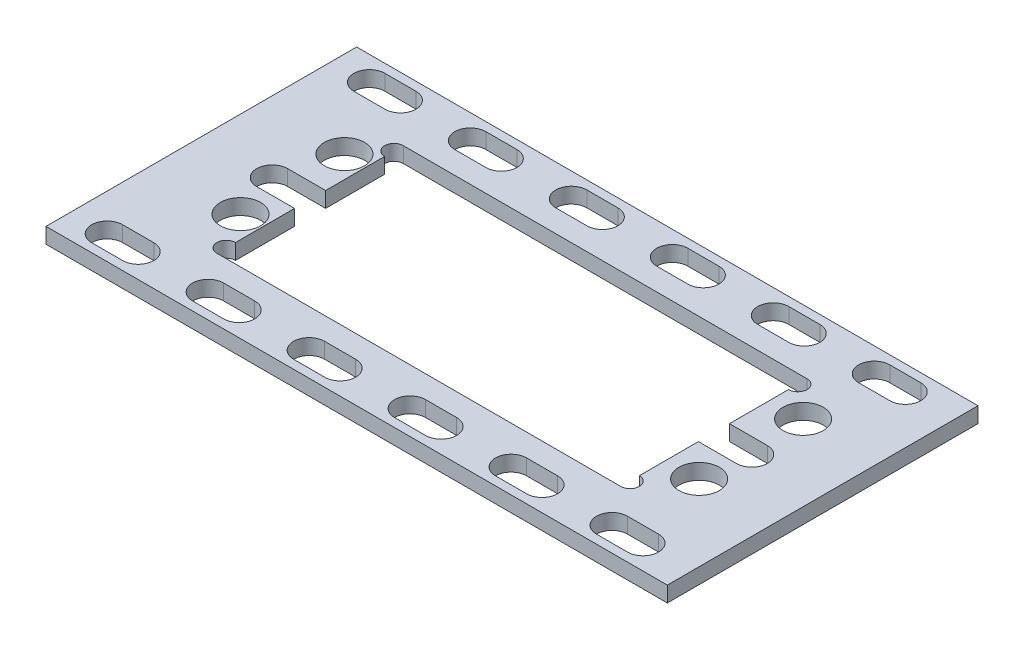
SolidWorks part; units mm, degrees
ref_plane "Front Plane" through (0, 0, 0) normal (0, 0, 1) x (1, 0, 0)
ref_plane "Top Plane" through (0, 0, 0) normal (0, 1, 0) x (1, 0, 0)
ref_plane "Right Plane" through (0, 0, 0) normal (1, 0, 0) x (0, 0, -1)
sketch "Sketch1" plane through (0, 0, 0) normal (0, 1, 0) x (1, 0, 0)
  line L0 (-33.02, 0) -> (33.02, 0) construction
  line L1 (-50.8, 25.4) -> (50.8, 25.4)
  line L2 (-50.8, 25.4) -> (-50.8, -25.4)
  line L3 (-50.8, -25.4) -> (50.8, -25.4)
  line L4 (50.8, 25.4) -> (50.8, -25.4)
  line L5 (-50.8, 25.4) -> (50.8, -25.4) construction
  line L6 (-50.8, -25.4) -> (50.8, 25.4) construction
  line L7 (-33.02, 15.24) -> (33.02, 15.24)
  line L8 (-33.02, 12.192) -> (-33.02, -12.192)
  line L9 (-33.02, -15.24) -> (33.02, -15.24)
  line L10 (33.02, 12.192) -> (33.02, -12.192)
  line L11 (-31.5887, 14.5794) -> (0, 0) construction
  line L12 (-33.02, -15.24) -> (33.02, 15.24) construction
  arc A0 (-33.02, 15.24) -> (-33.02, 12.192) centre (-33.02, 13.716) ccw
  arc A1 (-33.02, -12.192) -> (-33.02, -15.24) centre (-33.02, -13.716) ccw
  arc A2 (33.02, 12.192) -> (33.02, 15.24) centre (33.02, 13.716) ccw
  arc A3 (33.02, -15.24) -> (33.02, -12.192) centre (33.02, -13.716) ccw
  point P0 (0, 0)
  point P6 (0, 0)
  dimension "D5" = 1.524
  dimension "D6" = 1.524
  dimension "D1" = 101.6
  dimension "D2" = 50.8
  dimension "D3" = 66.04
  dimension "D4" = 30.48
extrude "Boss-Extrude1" add sketch "Sketch1" along normal blind 2.54
sketch "Sketch2" plane through (0, 2.54, 0) normal (0, 1, 0) x (1, 0, 0)
  line L0 (-44.7595, -21.439) -> (-39.6795, -21.439) construction
  line L1 (-44.7595, -18.899) -> (-39.6795, -18.899)
  line L2 (-44.7595, -23.979) -> (-39.6795, -23.979)
  line L3 (-28.2495, -23.979) -> (-23.1695, -23.979)
  line L4 (-28.2495, -18.899) -> (-23.1695, -18.899)
  line L5 (-28.2495, -21.439) -> (-23.1695, -21.439) construction
  line L6 (-11.7395, -23.979) -> (-6.6595, -23.979)
  line L7 (-11.7395, -18.899) -> (-6.6595, -18.899)
  line L8 (-11.7395, -21.439) -> (-6.6595, -21.439) construction
  line L9 (4.7705, -23.979) -> (9.8505, -23.979)
  line L10 (4.7705, -18.899) -> (9.8505, -18.899)
  line L11 (4.7705, -21.439) -> (9.8505, -21.439) construction
  line L12 (21.2805, -23.979) -> (26.3605, -23.979)
  line L13 (21.2805, -18.899) -> (26.3605, -18.899)
  line L14 (21.2805, -21.439) -> (26.3605, -21.439) construction
  line L15 (37.7905, -23.979) -> (42.8705, -23.979)
  line L16 (37.7905, -18.899) -> (42.8705, -18.899)
  line L17 (37.7905, -21.439) -> (42.8705, -21.439) construction
  line L18 (-50.8, 0) -> (50.607, 0) construction
  line L19 (-50.8, 25.4) -> (-50.8, -25.4) construction
  line L20 (-1.397, 0) -> (1.397, 0) construction
  line L21 (-28.2495, 21.439) -> (-23.1695, 21.439) construction
  line L22 (-28.2495, 18.899) -> (-23.1695, 18.899)
  line L23 (-28.2495, 23.979) -> (-23.1695, 23.979)
  line L24 (37.7905, 21.439) -> (42.8705, 21.439) construction
  line L25 (37.7905, 18.899) -> (42.8705, 18.899)
  line L26 (37.7905, 23.979) -> (42.8705, 23.979)
  line L27 (21.2805, 21.439) -> (26.3605, 21.439) construction
  line L28 (21.2805, 18.899) -> (26.3605, 18.899)
  line L29 (21.2805, 23.979) -> (26.3605, 23.979)
  line L30 (4.7705, 21.439) -> (9.8505, 21.439) construction
  line L31 (4.7705, 18.899) -> (9.8505, 18.899)
  line L32 (4.7705, 23.979) -> (9.8505, 23.979)
  line L33 (-11.7395, 21.439) -> (-6.6595, 21.439) construction
  line L34 (-11.7395, 18.899) -> (-6.6595, 18.899)
  line L35 (-11.7395, 23.979) -> (-6.6595, 23.979)
  line L36 (-44.7595, 21.439) -> (-39.6795, 21.439) construction
  line L37 (-44.7595, 18.899) -> (-39.6795, 18.899)
  line L38 (-44.7595, 23.979) -> (-39.6795, 23.979)
  arc A0 (-44.7595, -18.899) -> (-44.7595, -23.979) centre (-44.7595, -21.439) ccw
  arc A1 (-39.6795, -23.979) -> (-39.6795, -18.899) centre (-39.6795, -21.439) ccw
  arc A2 (-28.2495, -18.899) -> (-28.2495, -23.979) centre (-28.2495, -21.439) ccw
  arc A3 (-23.1695, -23.979) -> (-23.1695, -18.899) centre (-23.1695, -21.439) ccw
  arc A4 (-11.7395, -18.899) -> (-11.7395, -23.979) centre (-11.7395, -21.439) ccw
  arc A5 (-6.6595, -23.979) -> (-6.6595, -18.899) centre (-6.6595, -21.439) ccw
  arc A6 (4.7705, -18.899) -> (4.7705, -23.979) centre (4.7705, -21.439) ccw
  arc A7 (9.8505, -23.979) -> (9.8505, -18.899) centre (9.8505, -21.439) ccw
  arc A8 (21.2805, -18.899) -> (21.2805, -23.979) centre (21.2805, -21.439) ccw
  arc A9 (26.3605, -23.979) -> (26.3605, -18.899) centre (26.3605, -21.439) ccw
  arc A10 (37.7905, -18.899) -> (37.7905, -23.979) centre (37.7905, -21.439) ccw
  arc A11 (42.8705, -23.979) -> (42.8705, -18.899) centre (42.8705, -21.439) ccw
  arc A12 (-28.2495, 18.899) -> (-28.2495, 23.979) centre (-28.2495, 21.439) cw
  arc A13 (-23.1695, 23.979) -> (-23.1695, 18.899) centre (-23.1695, 21.439) cw
  arc A14 (37.7905, 18.899) -> (37.7905, 23.979) centre (37.7905, 21.439) cw
  arc A15 (42.8705, 23.979) -> (42.8705, 18.899) centre (42.8705, 21.439) cw
  arc A16 (21.2805, 18.899) -> (21.2805, 23.979) centre (21.2805, 21.439) cw
  arc A17 (26.3605, 23.979) -> (26.3605, 18.899) centre (26.3605, 21.439) cw
  arc A18 (4.7705, 18.899) -> (4.7705, 23.979) centre (4.7705, 21.439) cw
  arc A19 (9.8505, 23.979) -> (9.8505, 18.899) centre (9.8505, 21.439) cw
  arc A20 (-11.7395, 18.899) -> (-11.7395, 23.979) centre (-11.7395, 21.439) cw
  arc A21 (-6.6595, 23.979) -> (-6.6595, 18.899) centre (-6.6595, 21.439) cw
  arc A22 (-44.7595, 18.899) -> (-44.7595, 23.979) centre (-44.7595, 21.439) cw
  arc A23 (-39.6795, 23.979) -> (-39.6795, 18.899) centre (-39.6795, 21.439) cw
  point P2 (-42.2195, -21.439)
  point P11 (-25.7095, -21.439)
  point P18 (-9.1995, -21.439)
  point P25 (7.3105, -21.439)
  point P32 (23.8205, -21.439)
  point P39 (40.3305, -21.439)
  point P51 (-25.7095, 21.439)
  point P58 (40.3305, 21.439)
  point P65 (23.8205, 21.439)
  point P72 (7.3105, 21.439)
  point P79 (-9.1995, 21.439)
  point P86 (-42.2195, 21.439)
  dimension "D2" = 2.54
  dimension "D1" = 5.08
  dimension "D3" = 6
extrude "Cut-Extrude1" cut sketch "Sketch2" against normal through all
sketch "Sketch3" plane through (0, 2.54, 0) normal (0, 1, 0) x (1, 0, 0)
  line L0 (-33.02, 0) -> (-39.214, 0) construction
  line L1 (-33.02, 12.192) -> (-33.02, -12.192) construction
  line L2 (-1.397, 0) -> (1.397, 0) construction
  line L3 (-33.02, -2.54) -> (-39.214, -2.54)
  line L4 (-33.02, 2.54) -> (-39.214, 2.54)
  line L5 (0, -1.397) -> (0, 1.397) construction
  line L6 (33.02, 0) -> (39.214, 0) construction
  line L7 (33.02, -2.54) -> (39.214, -2.54)
  line L8 (33.02, 2.54) -> (39.214, 2.54)
  arc A0 (-33.02, -2.54) -> (-33.02, 2.54) centre (-33.02, 0) ccw
  arc A1 (-39.214, 2.54) -> (-39.214, -2.54) centre (-39.214, 0) ccw
  arc A2 (33.02, -2.54) -> (33.02, 2.54) centre (33.02, 0) cw
  arc A3 (39.214, 2.54) -> (39.214, -2.54) centre (39.214, 0) cw
  point P7 (-36.117, 0)
  point P16 (36.117, 0)
  dimension "D1" = 2.54
extrude "Cut-Extrude2" cut sketch "Sketch3" against normal through all
sketch "Sketch4" plane through (0, 2.54, 0) normal (0, 1, 0) x (1, 0, 0)
  circle A0 centre (-36.6339, -7.7637) radius 3.302
  circle A1 centre (-36.6339, 9.2363) radius 3.302
  circle A2 centre (38.3661, -7.7637) radius 3.302
  circle A3 centre (38.3661, 9.2363) radius 3.302
  dimension "D1" = 6.604
  dimension "D2" = 6.604
  dimension "D3" = 6.604
  dimension "D4" = 6.604
extrude "Cut-Extrude3" cut sketch "Sketch4" against normal through all
